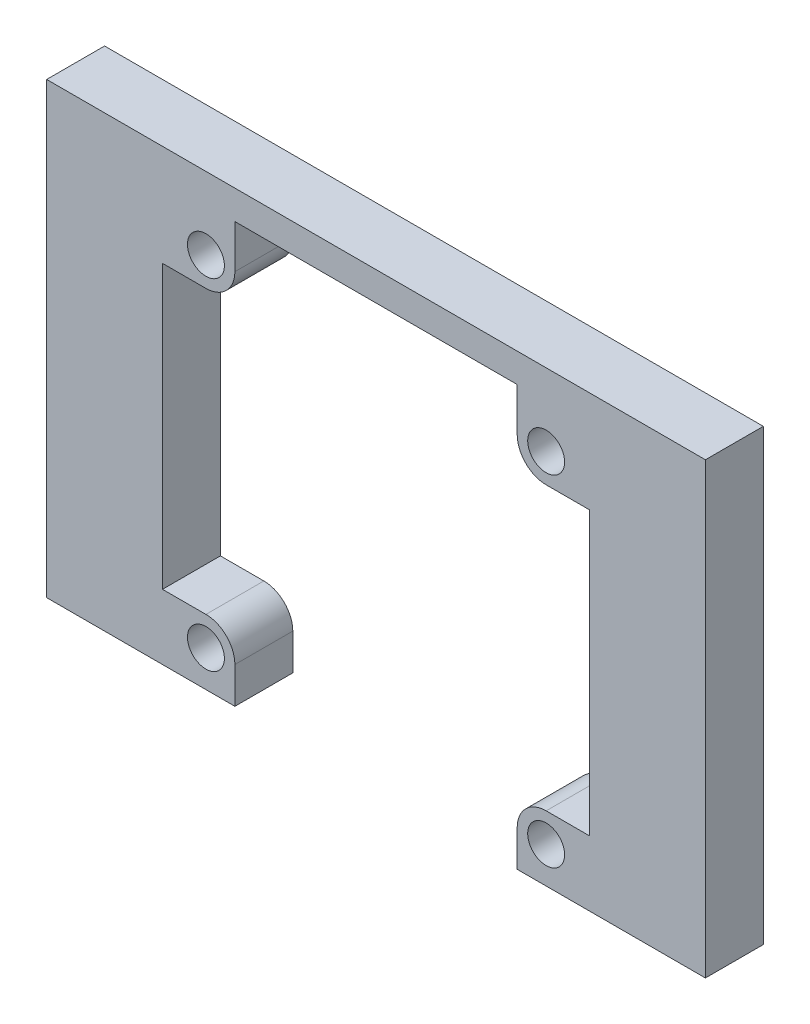
SolidWorks part; units mm, degrees
ref_plane "Plan de face" through (0, 0, 0) normal (0, 0, 1) x (1, 0, 0)
ref_plane "Plan de dessus" through (0, 0, 0) normal (0, 1, 0) x (1, 0, 0)
ref_plane "Plan de droite" through (0, 0, 0) normal (1, 0, 0) x (0, 0, -1)
sketch "Esquisse1" plane through (0, 0, 0) normal (0, 0, 1) x (1, 0, 0)
  line L0 (-35.8566, 30.95) -> (38.288, 30.95) construction
  line L5 (-45.5, -82.95) -> (45.5, 82.95) construction
  line L6 (-45.5, 82.95) -> (45.5, -82.95) construction
  line L11 (-65.5, -82.95) -> (65.5, 82.95) construction
  line L12 (-65.5, 82.95) -> (65.5, -82.95) construction
  line L17 (-28.5, 82.95) -> (28.5, 25.95) construction
  line L18 (-28.5, 25.95) -> (25.3031, 79.7531) construction
  line L19 (-35.8566, 77.95) -> (38.288, 77.95) construction
  line L20 (-23.5, 87.243) -> (-23.5, 12.7008) construction
  line L21 (23.5, 11.3093) -> (23.5, 87.243) construction
  line L22 (-28.5, 54.45) -> (28.5, 54.45) construction
  line L24 (-45.5, 26.95) -> (-45.5, 82.95)
  line L28 (45.5, 26.95) -> (45.5, 82.95)
  line L29 (-28.5, 72.95) -> (-28.5, 35.95)
  line L32 (-18.5, 77.95) -> (-18.5, 82.95)
  line L33 (-23.5, 72.95) -> (-28.5, 72.95)
  line L34 (18.5, 77.95) -> (18.5, 82.95)
  line L35 (23.5, 72.95) -> (28.5, 72.95)
  line L36 (23.5, 35.95) -> (28.5, 35.95)
  line L37 (18.5, 30.95) -> (18.5, 25.95)
  line L38 (-23.5, 35.95) -> (-28.5, 35.95)
  line L39 (-18.5, 30.95) -> (-18.5, 25.95)
  line L40 (-19.5, 77.95) -> (-19.5, 82.95)
  line L41 (-45.5, 25.95) -> (-45.5, 26.95)
  line L42 (28.5, 25.95) -> (45.5, 25.95)
  line L43 (45.5, 25.95) -> (45.5, 26.95)
  line L44 (-45.5, 82.95) -> (-45.5, 87.95)
  line L45 (-45.5, 87.95) -> (45.5, 87.95)
  line L46 (45.5, 87.95) -> (45.5, 82.95)
  line L47 (45.5, 25.95) -> (45.5, 20.95)
  line L49 (-19.5, 30.95) -> (-19.5, 24.95) construction
  line L50 (-18.5, 82.95) -> (18.5, 82.95)
  line L51 (-18.5, 82.95) -> (18.5, 82.95)
  line L52 (-18.5, 82.95) -> (18.5, 82.95)
  line L54 (28.5, 82.95) -> (45.5, 82.95)
  line L55 (28.5, 35.95) -> (28.5, 72.95)
  line L56 (-18.5, 25.95) -> (18.5, 25.95)
  line L57 (-23.5, 73.95) -> (-29.5, 73.95)
  line L58 (-29.5, 73.95) -> (-29.5, 34.95)
  line L59 (-23.5, 34.95) -> (-29.5, 34.95)
  line L60 (-19.5, 30.95) -> (-19.5, 25.95)
  line L62 (19.5, 30.95) -> (19.5, 25.95)
  line L63 (23.5, 34.95) -> (29.5, 34.95)
  line L64 (29.5, 34.95) -> (29.5, 73.95)
  line L65 (23.5, 73.95) -> (29.5, 73.95)
  line L66 (19.5, 77.95) -> (19.5, 82.95)
  line L67 (-18.5, 83.95) -> (18.5, 83.95)
  line L68 (-19.5, 82.95) -> (-19.5, 83.95)
  line L69 (-19.5, 83.95) -> (-18.5, 83.95)
  line L70 (18.5, 83.95) -> (19.5, 83.95)
  line L71 (19.5, 83.95) -> (19.5, 82.95)
  line L72 (-18.5, 25.95) -> (-45.5, 25.95)
  line L73 (18.5, 25.95) -> (45.5, 25.95)
  line L74 (-19.5, 24.95) -> (19.5, 24.95) construction
  line L75 (19.5, 30.95) -> (19.5, 24.95) construction
  circle A1 centre (-23.5, 30.95) radius 2.55
  circle A2 centre (23.5, 77.95) radius 2.55
  circle A3 centre (23.5, 30.95) radius 2.55
  circle A4 centre (-23.5, 77.95) radius 2.55
  arc A5 (-23.5, 72.95) -> (-18.5, 77.95) centre (-23.5, 77.95) ccw
  arc A6 (18.5, 77.95) -> (23.5, 72.95) centre (23.5, 77.95) ccw
  arc A7 (-18.5, 30.95) -> (-23.5, 35.95) centre (-23.5, 30.95) ccw
  arc A8 (23.5, 35.95) -> (18.5, 30.95) centre (23.5, 30.95) ccw
  arc A9 (-23.5, 73.95) -> (-19.5, 77.95) centre (-23.5, 77.95) ccw
  arc A10 (-19.5, 30.95) -> (-23.5, 34.95) centre (-23.5, 30.95) ccw
  arc A11 (23.5, 34.95) -> (19.5, 30.95) centre (23.5, 30.95) ccw
  arc A12 (19.5, 77.95) -> (23.5, 73.95) centre (23.5, 77.95) ccw
  point P0 (0, 0)
  point P6 (0, 0)
  point P11 (0, 54.45)
  dimension "D14" = 5.1
  dimension "D10" = 10
  dimension "D1" = 91
  dimension "D2" = 165.9
  dimension "D4" = 165.9
  dimension "D5" = 57
  dimension "D6" = 57
  dimension "D3" = 1
  dimension "D7" = 1
extrude "Boss.-Extru.2" add sketch "Esquisse1" along normal blind 8
equation "\"D4@Esquisse1\"=\"D2@Esquisse1\""
